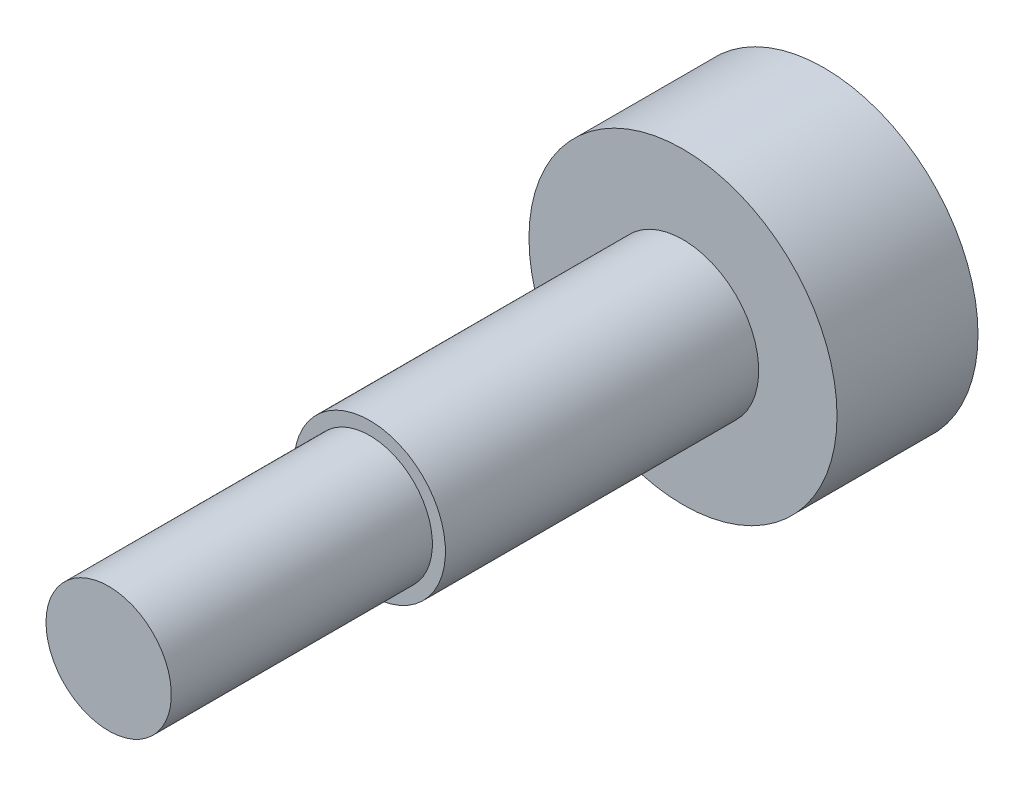
SolidWorks part; units mm, degrees
ref_plane "前视基准面" through (0, 0, 0) normal (0, 0, 1) x (1, 0, 0)
ref_plane "上视基准面" through (0, 0, 0) normal (0, 1, 0) x (1, 0, 0)
ref_plane "右视基准面" through (0, 0, 0) normal (1, 0, 0) x (0, 0, -1)
other "Configuration Table"
sketch "草图1" plane through (0, 0, 0) normal (0, 1, 0) x (1, 0, 0)
  line L0 (0, 34.4303) -> (0, -35.6466) construction
  line L5 (0, 0) -> (1.2, 0)
  line L6 (0, 0) -> (0, -5)
  line L7 (0, -5) -> (1.2, -5)
  line L8 (1.2, 0) -> (1.2, -5)
  line L9 (0, 0) -> (1.45, 0)
  line L10 (0, 0) -> (0, 6)
  line L11 (0, 6) -> (1.45, 6)
  line L12 (1.45, 0) -> (1.45, 6)
  line L13 (0, 6) -> (2.95, 6)
  line L14 (0, 6) -> (0, 8.7)
  line L15 (0, 8.7) -> (2.95, 8.7)
  line L16 (2.95, 6) -> (2.95, 8.7)
  dimension "D3" = 1.45
  dimension "D4" = 6
  dimension "D1" = 5
  dimension "D2" = 1.2
  dimension "D5" = 2.7
  dimension "D6" = 2.95
revolve "旋转1" add sketch "草图1" angle 360 about L0
